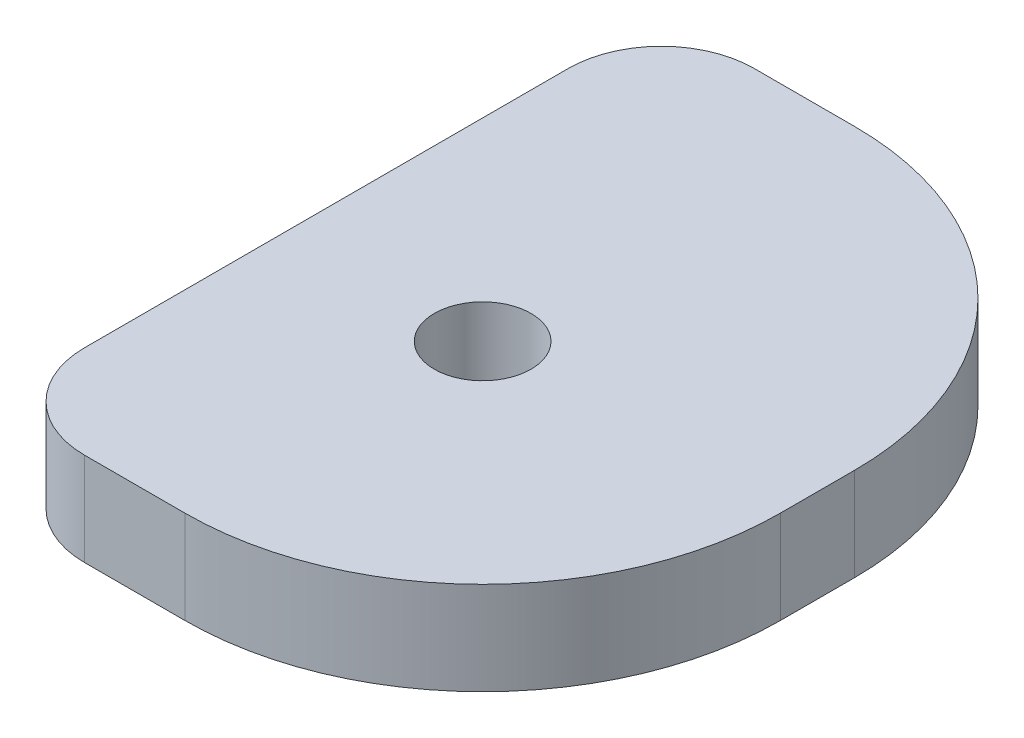
SolidWorks part; units mm, degrees
ref_plane "Front Plane" through (0, 0, 0) normal (0, 0, 1) x (1, 0, 0)
ref_plane "Top Plane" through (0, 0, 0) normal (0, 1, 0) x (1, 0, 0)
ref_plane "Right Plane" through (0, 0, 0) normal (1, 0, 0) x (0, 0, -1)
sketch "Sketch1" plane through (0, 0, 0) normal (0, 1, 0) x (1, 0, 0)
  line L1 (-25.4, 11.43) -> (25.4, 11.43)
  line L2 (-25.4, 11.43) -> (-25.4, -11.43)
  line L3 (-25.4, -11.43) -> (25.4, -11.43)
  line L4 (25.4, 11.43) -> (25.4, -11.43)
  dimension "D1" = 22.86
  dimension "D2" = 50.8
  dimension "D3" = 11.43
  dimension "D4" = 25.4
extrude "Boss-Extrude1" add sketch "Sketch1" along normal blind 3.175
fillet "Fillet1" radius 10.16 2 edges at (-25.4, 1.5875, 11.43) (25.4, 1.5875, 11.43)
sketch "Sketch3" plane through (0, 3.175, 0) normal (0, 1, 0) x (1, 0, 0)
  line L0 (-7.7526, -1.27) -> (18.5521, -1.27) construction
  circle A0 centre (15.24, -1.27) radius 1.651
  arc A2 (15.24, -11.43) -> (25.4, -1.27) centre (15.24, -1.27) ccw construction
  circle A3 centre (-3.81, -1.27) radius 1.651
  dimension "D1" = 3.302
  dimension "D6" = 3.302
  dimension "D5" = 19.05
extrude "Cut-Extrude1" cut sketch "Sketch3" against normal through all
fillet "Fillet3" radius 10.16 2 edges at (-25.4, 1.5875, -11.43) (25.4, 1.5875, -11.43)
sketch "Sketch4" plane through (0, 0, 0) normal (0, -1, 0) x (-1, 0, 0)
  line L0 (15.24, -11.43) -> (-15.24, -11.43) construction
  line L1 (-8.636, -11.43) -> (25.4, -11.43)
  line L2 (-8.636, -11.43) -> (-8.636, 11.43)
  line L3 (-8.636, 11.43) -> (25.4, 11.43)
  line L4 (25.4, -11.43) -> (25.4, 11.43)
  line L5 (25.4, 1.27) -> (25.4, -1.27) construction
  line L6 (-15.24, 11.43) -> (15.24, 11.43) construction
  line L7 (-25.4, -1.27) -> (-25.4, 1.27) construction
  dimension "D1" = 16.764
extrude "Cut-Extrude2" cut sketch "Sketch4" against normal through all
fillet "Fillet4" radius 3.175 2 edges at (8.636, 1.5875, 11.43) (8.636, 1.5875, -11.43)
equation "\"D4@Sketch1\"=\"D2@Sketch1\"/2"
equation "\"D3@Sketch1\"=\"D1@Sketch1\"/2"
